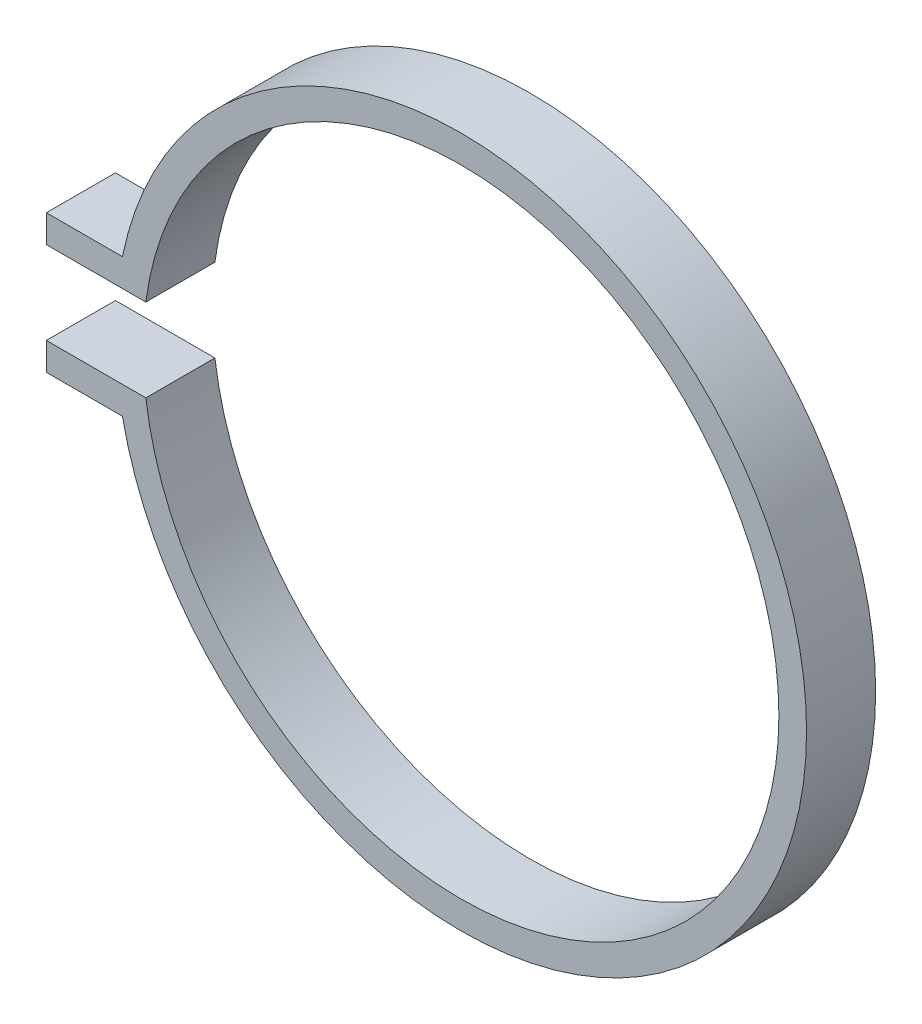
SolidWorks part; units mm, degrees
ref_plane "Front Plane" through (0, 0, 0) normal (0, 0, 1) x (1, 0, 0)
ref_plane "Top Plane" through (0, 0, 0) normal (0, 1, 0) x (1, 0, 0)
ref_plane "Right Plane" through (0, 0, 0) normal (1, 0, 0) x (0, 0, -1)
sketch "Sketch1" plane through (0, 0, 0) normal (0, 0, 1) x (1, 0, 0)
  line L0 (0, 0) -> (74556.4033, 0) construction
  line L1 (0, 0) -> (0, 74556.4033) construction
  line L2 (-60, 10) -> (-48.9898, 10)
  line L3 (-60, -10) -> (-48.9898, -10)
  line L4 (-60, 6) -> (-45.607, 6)
  line L5 (-60, -6) -> (-45.607, -6)
  line L6 (-60, 10) -> (-60, 6)
  line L7 (-60, -6) -> (-60, -10)
  line L8 (-60, 10) -> (-39.8061, 10) construction
  line L9 (-60, 6) -> (-39.8061, 6) construction
  line L10 (-60, -6) -> (-39.8061, -6) construction
  line L11 (-60, -10) -> (-39.8061, -10) construction
  arc A0 (-48.9898, -10) -> (-48.9898, 10) centre (0, 0) ccw
  arc A1 (-45.607, -6) -> (-45.607, 6) centre (0, 0) ccw
  point P12 (0, 0)
  dimension "D1" = 100
  dimension "D2" = 92
  dimension "D3" = 20
  dimension "D6" = 60
  dimension "D4" = 4
  dimension "D5" = 4
extrude "Boss-Extrude1" add sketch "Sketch1" along normal blind 10
